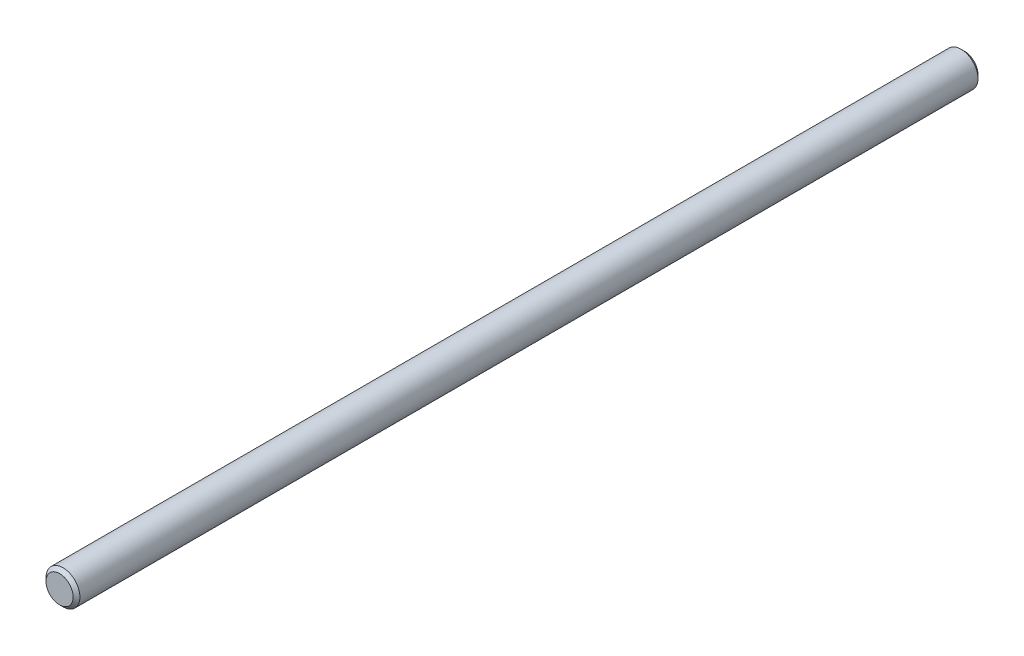
SolidWorks part; units mm, degrees
ref_plane "Front" through (0, 0, 0) normal (0, 0, 1) x (1, 0, 0)
ref_plane "Top" through (0, 0, 0) normal (0, 1, 0) x (1, 0, 0)
ref_plane "Right" through (0, 0, 0) normal (1, 0, 0) x (0, 0, -1)
sketch "Sketch1" plane through (0, 0, 0) normal (0, 0, 1) x (1, 0, 0)
  circle A0 centre (0, 0) radius 4.7625
  dimension "Diameter" = 9.525
sketch "Sketch2" plane through (0, 0, 0) normal (1, 0, 0) x (0, 0, -1)
  line L0 (-127, 0) -> (127, 0) construction
  line L1 (-76.2, 4.7625) -> (-76.2, -4.7625) construction
  line L2 (5.2387, 0) -> (-5.2387, 0) construction
  line L3 (76.2, 4.7625) -> (76.2, -4.7625) construction
  line L4 (-127, 4.7625) -> (-127, -4.7625) construction
  line L5 (127, 4.7625) -> (127, -4.7625) construction
  point P3 (-76.2, 0)
  point P8 (0, 0)
  point P9 (76.2, 0)
  point P15 (-127, 0)
  point P18 (127, 0)
  dimension "D1" = 9.525
  dimension "Length" = 254
  dimension "D2" = 50.8
  dimension "D3" = 50.8
sketch "Sketch3" plane through (0, 0, 0) normal (0, 0, 1) x (1, 0, 0)
  circle A0 centre (0, 0) radius 4.7625
  dimension "D1" = 9.525
extrude "Boss-Extrude1" add sketch "Sketch3" along normal mid plane 254
chamfer "Chamfer1" distance 0.9525 angle 45 2 edges at (4.7625, 0, -127) (4.7625, 0, 127)
equation "\"D1@Sketch3\" = \"Diameter@Sketch1\""
equation "\"D1@Boss-Extrude1\" = \"Length@Sketch2\""
equation "\"D1@Chamfer1\" = \"Diameter@Sketch1\" * .1"
equation "\"D1@Sketch2\" = \"Diameter@Sketch1\""
